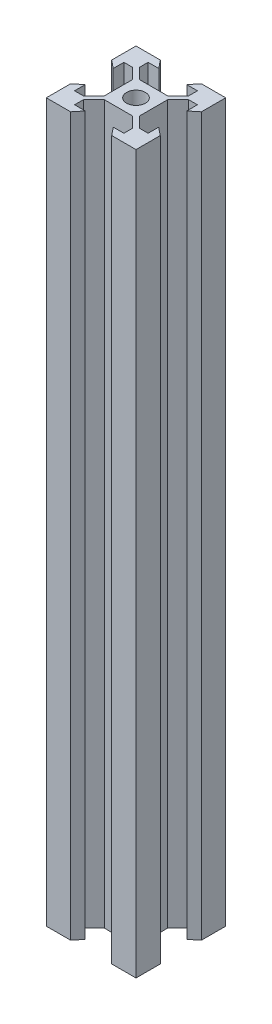
SolidWorks part; units mm, degrees
ref_plane "Front Plane" through (0, 0, 0) normal (0, 0, 1) x (1, 0, 0)
ref_plane "Top Plane" through (0, 0, 0) normal (0, 1, 0) x (1, 0, 0)
ref_plane "Right Plane" through (0, 0, 0) normal (1, 0, 0) x (0, 0, -1)
sketch "Sketch1" plane through (0, 0, 0) normal (0, 1, 0) x (1, 0, 0)
  line L0 (0, 0) -> (5.42, 0)
  line L2 (20, 20) -> (14.58, 20)
  line L3 (0, 20) -> (0, 14.58)
  line L5 (0, 5.415) -> (1.8, 6.875)
  line L6 (15.5, 18.2) -> (13.125, 18.2)
  line L7 (6.1, 6.85) -> (6.1, 13.15)
  line L8 (1.8, 15.5) -> (1.8, 13.12)
  line L10 (4.5, 1.8) -> (6.875, 1.8)
  line L12 (18.2, 4.5) -> (18.2, 5.415)
  line L17 (13.1475, 1.8) -> (15.5, 1.8)
  line L18 (13.9, 13.15) -> (13.9, 6.85)
  line L21 (13.15, 13.9) -> (6.85, 13.9)
  line L23 (6.85, 6.1) -> (13.15, 6.1)
  line L25 (6.875, 18.2) -> (4.5, 18.2)
  line L26 (0, 5.415) -> (0, 0)
  line L27 (6.1, 13.15) -> (3.75, 15.5)
  line L28 (6.85, 13.9) -> (4.5, 16.25)
  line L29 (13.15, 13.9) -> (15.5, 16.25)
  line L30 (15.5, 18.2) -> (13.125, 18.2)
  line L31 (4.5, 3.75) -> (6.85, 6.1)
  line L32 (6.1, 6.85) -> (3.75, 4.5)
  line L33 (0, 14.58) -> (0, 14.7)
  line L35 (18.2, 13.12) -> (18.2, 15.5)
  line L37 (16.25, 4.5) -> (13.9, 6.85)
  line L38 (15.5, 3.75) -> (13.15, 6.1)
  line L40 (5.42, 20) -> (0, 20)
  line L41 (13.9, 13.15) -> (16.25, 15.5)
  line L42 (18.2, 15.5) -> (18.2, 13.12)
  line L43 (14.58, 0) -> (20, 0)
  line L44 (14.58, 20) -> (20, 20)
  line L45 (1.8, 6.875) -> (1.8, 5.415)
  line L46 (5.42, 20) -> (6.875, 18.2)
  line L47 (13.125, 18.2) -> (14.58, 20)
  line L50 (14.58, 20) -> (20, 20)
  line L54 (5.42, 0) -> (6.875, 1.8)
  line L55 (18.2, 13.12) -> (18.2, 15.5)
  line L56 (13.1475, 1.8) -> (14.58, 0)
  line L57 (15.5, 18.2) -> (13.125, 18.2)
  line L58 (4.5, 18.2) -> (6.875, 18.2)
  line L59 (1.8, 15.5) -> (1.8, 13.12)
  line L60 (4.5, 18.2) -> (6.875, 18.2)
  line L61 (1.8, 15.5) -> (1.8, 13.12)
  line L62 (5.42, 20) -> (6.875, 18.2)
  line L63 (1.8, 13.12) -> (1.8, 14.7)
  line L64 (18.2, 5.415) -> (18.2, 4.5)
  line L65 (4.5, 18.2) -> (6.875, 18.2)
  line L69 (1.8, 13.12) -> (1.8, 13.125)
  line L70 (20, 5.415) -> (20, 0)
  line L71 (1.8, 14.7) -> (1.8, 13.12)
  line L72 (1.8, 13.12) -> (1.8, 13.125)
  line L73 (0, 5.415) -> (1.8, 6.875)
  line L74 (13.1475, 1.8) -> (15.5, 1.8)
  line L75 (14.58, 20) -> (20, 20)
  line L79 (1.8, 14.7) -> (1.8, 15.5)
  line L80 (5.42, 0) -> (6.875, 1.8)
  line L81 (15.5, 18.2) -> (13.125, 18.2)
  line L82 (1.8, 15.5) -> (1.8, 14.58)
  line L83 (18.2, 15.5) -> (18.2, 13.12)
  line L84 (15.5, 1.8) -> (13.1475, 1.8)
  line L85 (1.8, 14.58) -> (1.8, 13.125)
  line L86 (18.2, 13.12) -> (20, 14.58)
  line L87 (1.8, 13.125) -> (0, 14.58)
  line L89 (1.8, 13.125) -> (1.8, 13.12)
  line L91 (1.8, 14.58) -> (1.8, 13.12)
  line L92 (1.8, 14.58) -> (1.8, 13.12)
  line L94 (1.8, 14.58) -> (1.8, 13.12)
  line L98 (0, 20) -> (4.5, 20)
  line L99 (1.8, 5.415) -> (1.8, 4.5)
  line L100 (18.2, 6.85) -> (18.2, 6.8625)
  line L101 (18.2, 4.5) -> (18.2, 5.415)
  line L102 (18.2154, 6.8625) -> (18.2, 6.8625)
  line L108 (1.8, 13.12) -> (1.8, 13.125)
  line L110 (6.85, 13.9) -> (13.15, 13.9)
  line L111 (18.2, 6.85) -> (18.2, 6.8625)
  line L112 (4.5, 18.2) -> (4.5, 16.25)
  line L113 (18.2, 5.415) -> (18.2, 6.8625)
  line L114 (3.75, 15.5) -> (1.8, 15.5)
  line L115 (20, 5.415) -> (18.2, 6.85)
  line L116 (1.8, 15.5) -> (3.75, 15.5)
  line L117 (20, 20) -> (20, 14.58)
  line L118 (6.1, 13.15) -> (6.1, 6.85)
  line L119 (6.85, 6.1) -> (13.15, 6.1)
  line L120 (20, 14.58) -> (20, 20)
  line L121 (0, 20) -> (4.5, 20)
  line L122 (20, 20) -> (15.5, 20)
  line L125 (15.5, 18.2) -> (15.5, 16.25)
  line L128 (20, 0) -> (20, 4.5)
  line L131 (1.8, 5.415) -> (1.8, 4.5)
  line L132 (6.875, 1.8) -> (4.5, 1.8)
  line L133 (4.5, 1.8) -> (6.875, 1.8)
  line L134 (18.2, 4.5) -> (16.25, 4.5)
  line L135 (15.5, 3.75) -> (15.5, 1.8)
  line L136 (6.875, 1.8) -> (4.5, 1.8)
  line L137 (0, 0) -> (4.5, 0)
  line L138 (4.5, 1.8) -> (4.5, 3.75)
  line L139 (3.75, 4.5) -> (1.8, 4.5)
  line L140 (16.25, 15.5) -> (18.2, 15.5)
  circle A0 centre (10, 10) radius 2.1
extrude "Boss-Extrude1" add sketch "Sketch1" along normal blind 160 contours L41 L140 L35 L86 L117 L2 L75 L47 L6 L125 L29 L21 L28 L112 L25 L46 L40 L3 L87 L71 L61 L8 L114 L27 L7 L32 L139 L99 L45 L5 L26 L0 L54 L10 L138 L31 L23 L38 L135 L17 L56 L43 L70 L115 L113 L12 L134
